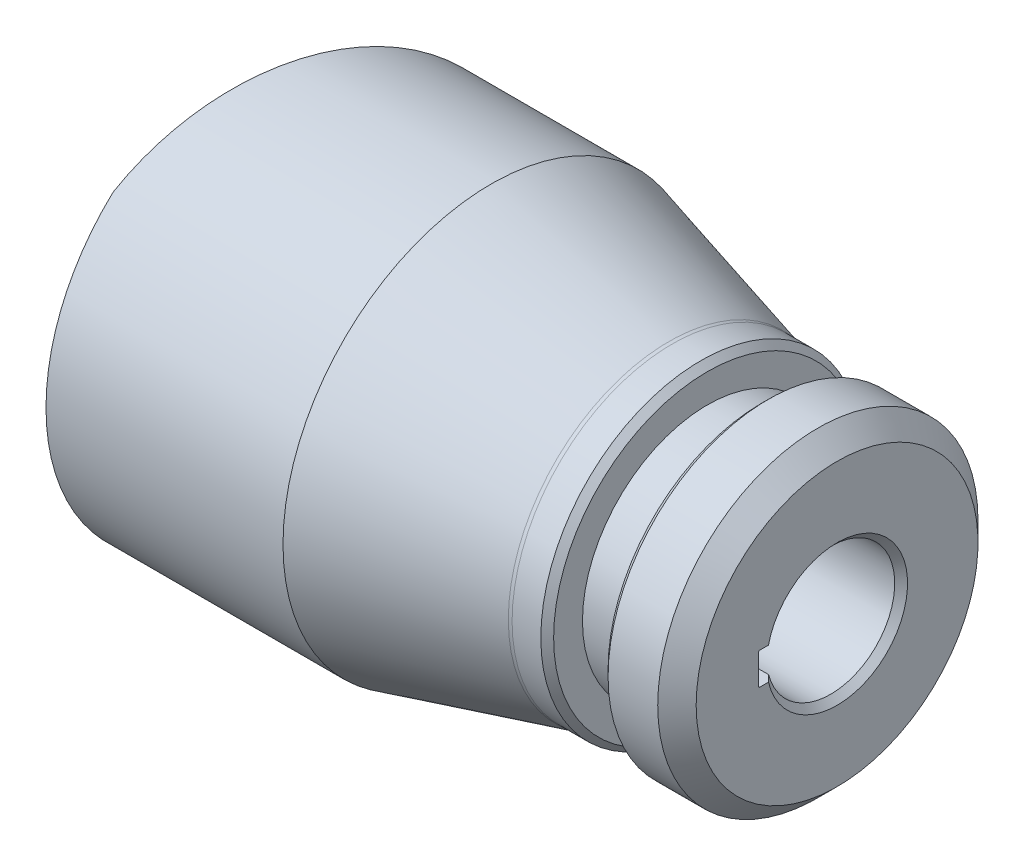
SolidWorks part; units mm, degrees
ref_plane "Спереди" through (0, 0, 0) normal (0, 0, 1) x (1, 0, 0)
ref_plane "Сверху" through (0, 0, 0) normal (0, 1, 0) x (1, 0, 0)
ref_plane "Справа" through (0, 0, 0) normal (1, 0, 0) x (0, 0, -1)
other "Configuration Table"
sketch "Эскиз1" plane through (0, 0, 0) normal (0, 0, 1) x (1, 0, 0)
  line L0 (0, 32.5) -> (37, 32.5)
  line L1 (37, 32.5) -> (64.7457, 25.0681)
  line L2 (65.2632, 25) -> (69.75, 25)
  line L3 (69.75, 25) -> (70.75, 24)
  line L4 (70.75, 24) -> (70.75, 19.5)
  line L5 (70.75, 19.5) -> (79.25, 19.5)
  line L6 (79.25, 19.5) -> (79.25, 24)
  line L7 (79.25, 24) -> (80.25, 25)
  line L8 (80.25, 25) -> (88, 25)
  line L9 (88, 25) -> (91, 22)
  line L10 (91, 22) -> (91, 11)
  line L11 (91, 11) -> (90, 10)
  line L12 (90, 10) -> (61, 10)
  line L13 (61, 10) -> (61, 19)
  line L14 (60, 20) -> (25, 20)
  line L15 (25, 20) -> (25, 27.1)
  line L16 (24.6, 27.5) -> (0, 27.5)
  line L17 (0, 27.5) -> (0, 32.5)
  line L18 (0, 0) -> (100, 0) construction
  arc A0 (64.7457, 25.0681) -> (65.2632, 25) centre (65.2632, 27) ccw
  arc A1 (61, 19) -> (60, 20) centre (60, 19) ccw
  arc A2 (25, 27.1) -> (24.6, 27.5) centre (24.6, 27.1) ccw
revolve "Точеный профиль" add sketch "Эскиз1" angle 360 about L18
sketch "Эскиз2" plane through (0, 0, 0) normal (0, 1, 0) x (1, 0, 0)
  line L0 (-25, 50) -> (15.3041, 50)
  line L1 (15.3041, 50) -> (-5.9516, -50)
  line L2 (-5.9516, -50) -> (-25, -50)
  line L3 (-25, -50) -> (-25, 50)
extrude "Наклон торца 12 градусов" cut sketch "Эскиз2" against normal through all and the other way through all
sketch "Эскиз3" plane through (0, 0, 0) normal (1, 0, 0) x (0, 0, -1)
  line L0 (0, -2.5) -> (0, 2.5)
  line L1 (0, 2.5) -> (-12.05, 2.5)
  line L2 (-12.3, 2.25) -> (-12.3, -2.25)
  line L3 (-12.05, -2.5) -> (0, -2.5)
  arc A0 (-12.05, 2.5) -> (-12.3, 2.25) centre (-12.05, 2.25) ccw
  arc A1 (-12.3, -2.25) -> (-12.05, -2.5) centre (-12.05, -2.25) ccw
extrude "Паз 5 R0.25" cut sketch "Эскиз3" along normal blind 31 from offset 61
